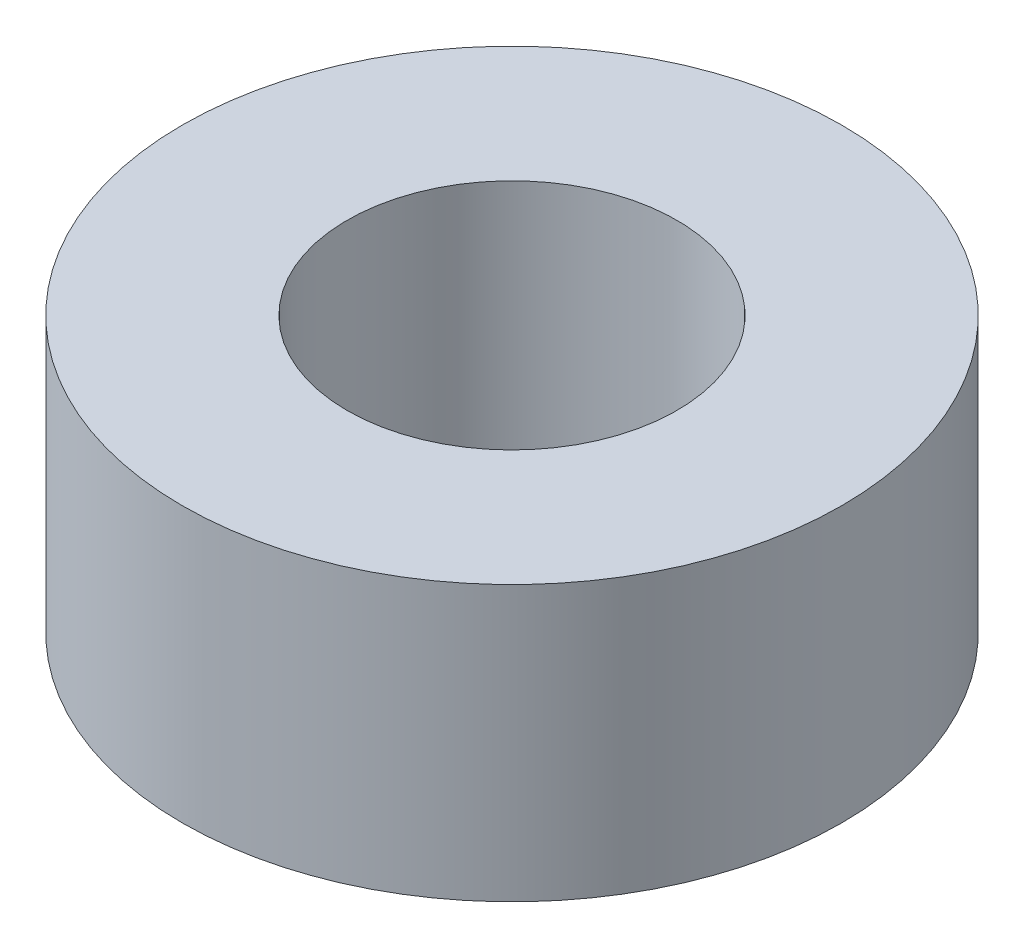
SolidWorks part; units mm, degrees
material "铸造不锈钢"
ref_plane "前视基准面" through (0, 0, 0) normal (0, 0, 1) x (1, 0, 0)
ref_plane "上视基准面" through (0, 0, 0) normal (0, 1, 0) x (1, 0, 0)
ref_plane "右视基准面" through (0, 0, 0) normal (1, 0, 0) x (0, 0, -1)
other "Configuration Table"
sketch "草图1" plane through (0, 0, 0) normal (0, 1, 0) x (1, 0, 0)
  circle A0 centre (0, 0) radius 1.5
  circle A1 centre (0, 0) radius 3
  dimension "D1" = 6
  dimension "D2" = 3
extrude "凸台-拉伸1" add sketch "草图1" along normal blind 2.5
